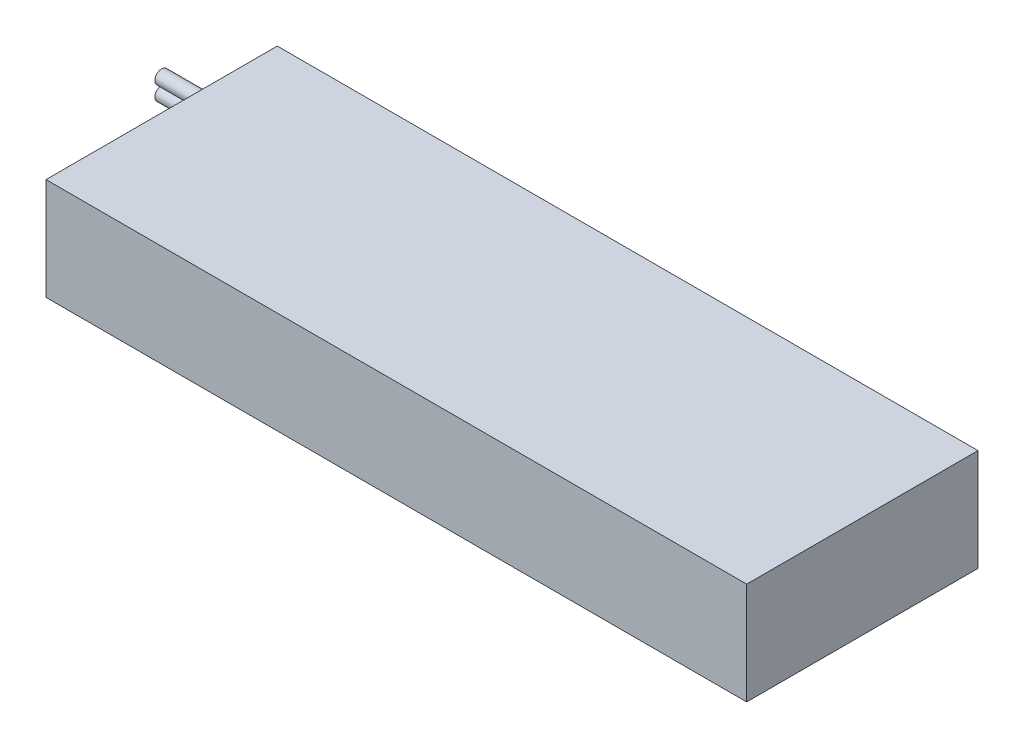
SolidWorks part; units mm, degrees
ref_plane "Front Plane" through (0, 0, 0) normal (0, 0, 1) x (1, 0, 0)
ref_plane "Top Plane" through (0, 0, 0) normal (0, 1, 0) x (1, 0, 0)
ref_plane "Right Plane" through (0, 0, 0) normal (1, 0, 0) x (0, 0, -1)
sketch "Sketch1" plane through (0, 0, 0) normal (0, 0, 1) x (1, 0, 0)
  line L1 (0, 0) -> (103, 0)
  line L2 (0, 0) -> (0, 15)
  line L3 (0, 15) -> (103, 15)
  line L4 (103, 0) -> (103, 15)
  dimension "D1" = 103
  dimension "D2" = 15
extrude "Boss-Extrude1" add sketch "Sketch1" along normal blind 34
sketch "Sketch2" plane through (0, 0, 0) normal (-1, 0, 0) x (0, 0, 1)
  line L0 (2, 4.6) -> (2, 2.5) construction
  line L1 (34, 0) -> (0, 0) construction
  line L2 (0, 15) -> (0, 0) construction
  circle A0 centre (2, 2.5) radius 1
  circle A1 centre (2, 4.6) radius 1
  dimension "D1" = 2
  dimension "D2" = 2.1
  dimension "D3" = 2.5
  dimension "D4" = 2
extrude "Boss-Extrude2" add sketch "Sketch2" along normal blind 15
